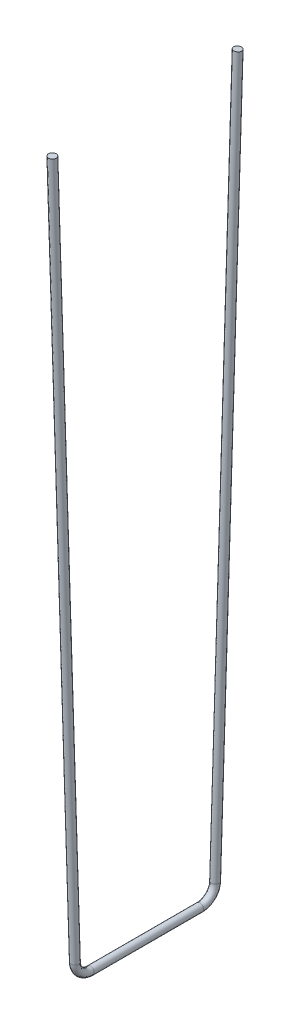
SolidWorks part; units mm, degrees
ref_plane "Front Plane" through (0, 0, 0) normal (0, 0, 1) x (1, 0, 0)
ref_plane "Top Plane" through (0, 0, 0) normal (0, 1, 0) x (1, 0, 0)
ref_plane "Right Plane" through (0, 0, 0) normal (1, 0, 0) x (0, 0, -1)
sketch "Sketch1" plane through (0, 0, 0) normal (0, 1, 0) x (1, 0, 0)
  circle A0 centre (0, 0) radius 2.5
  dimension "D1" = 5
sketch "Sketch2" plane through (0, 0, 0) normal (1, 0, 0) x (0, 0, -1)
  line L0 (0, 0) -> (14.5866, -459.4704)
  line L1 (24.5816, -469.1531) -> (95.4184, -469.1531)
  line L2 (105.4134, -459.4704) -> (120, 0)
  arc A0 (14.5866, -459.4704) -> (24.5816, -469.1531) centre (24.5816, -459.1531) ccw
  arc A1 (95.4184, -469.1531) -> (105.4134, -459.4704) centre (95.4184, -459.1531) ccw
  point P2 (60, -469.1531)
  point P7 (48.7574, -469.1531)
  dimension "D2" = 10
  dimension "D5" = 10
  dimension "D1" = 120
  dimension "D3" = 60
  dimension "D4" = 469.1531
sweep "Sweep3" add profiles "Sketch1" path "Sketch2"
ref_plane "Plane3" through (130, 0, 0) normal (1, 0, 0) x (0, 0, -1)
